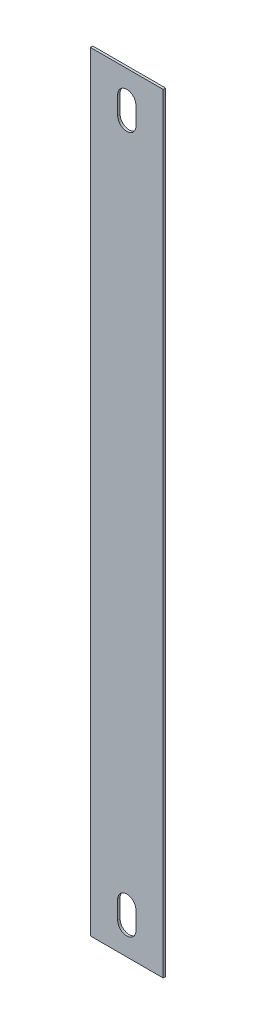
SolidWorks part; units mm, degrees
ref_plane "Front Plane" through (0, 0, 0) normal (0, 0, 1) x (1, 0, 0)
ref_plane "Top Plane" through (0, 0, 0) normal (0, 1, 0) x (1, 0, 0)
ref_plane "Right Plane" through (0, 0, 0) normal (1, 0, 0) x (0, 0, -1)
sketch "Sketch1" plane through (0, 0, 0) normal (0, 0, 1) x (1, 0, 0)
  line L1 (30, -317.32) -> (-30, -317.32)
  line L2 (30, -317.32) -> (30, 317.32)
  line L3 (30, 317.32) -> (-30, 317.32)
  line L4 (-30, -317.32) -> (-30, 317.32)
  line L5 (30, -317.32) -> (-30, 317.32) construction
  line L6 (30, 317.32) -> (-30, -317.32) construction
  point P0 (0, 0)
  dimension "D1" = 60
  dimension "D2" = 634.64
extrude "Boss-Extrude1" add sketch "Sketch1" along normal blind 2
sketch "Sketch2" plane through (0, 0, 2) normal (0, 0, 1) x (1, 0, 0)
  line L0 (0, 294.82) -> (0, 279.82) construction
  line L1 (7.5, 294.82) -> (7.5, 279.82)
  line L2 (-7.5, 294.82) -> (-7.5, 279.82)
  line L3 (30, 317.32) -> (-30, 317.32) construction
  line L4 (0, 0) -> (-305.2544, 0) construction
  line L5 (0, -294.82) -> (0, -279.82) construction
  line L6 (7.5, -294.82) -> (7.5, -279.82)
  line L7 (-7.5, -294.82) -> (-7.5, -279.82)
  arc A0 (7.5, 294.82) -> (-7.5, 294.82) centre (0, 294.82) ccw
  arc A1 (-7.5, 279.82) -> (7.5, 279.82) centre (0, 279.82) ccw
  arc A2 (7.5, -294.82) -> (-7.5, -294.82) centre (0, -294.82) cw
  arc A3 (-7.5, -279.82) -> (7.5, -279.82) centre (0, -279.82) cw
  point P3 (0, 287.32)
  point P8 (0, 302.32)
  point P9 (0, 272.32)
  point P16 (0, -287.32)
  dimension "D1" = 30
  dimension "D2" = 15
  dimension "D3" = 15
extrude "Cut-Extrude1" cut sketch "Sketch2" against normal up to next
